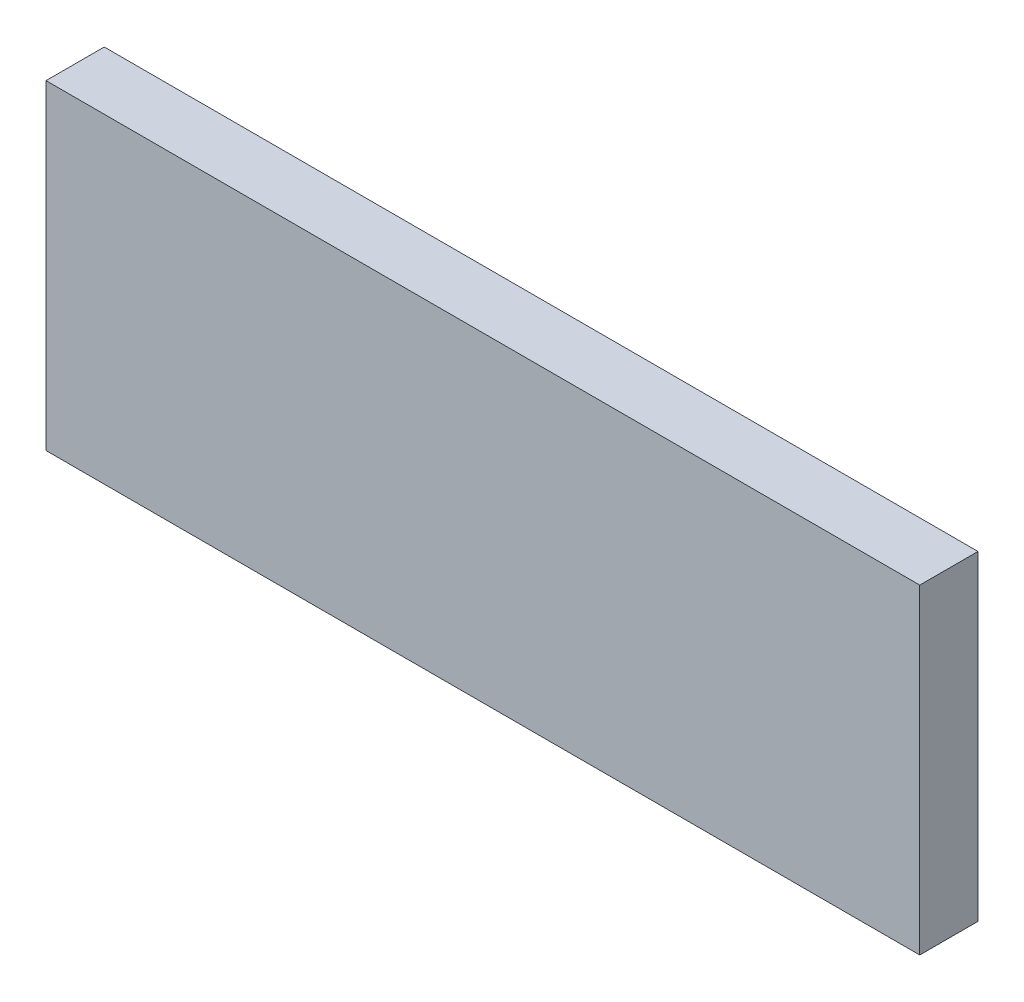
SolidWorks part; units mm, degrees
ref_plane "Front Plane" through (0, 0, 0) normal (0, 0, 1) x (1, 0, 0)
ref_plane "Top Plane" through (0, 0, 0) normal (0, 1, 0) x (1, 0, 0)
ref_plane "Right Plane" through (0, 0, 0) normal (1, 0, 0) x (0, 0, -1)
sketch "Sketch1" plane through (0, 0, 0) normal (0, 0, 1) x (1, 0, 0)
  line L1 (-51.24, 31.58) -> (-21.24, 31.58)
  line L2 (-51.24, 31.58) -> (-51.24, 20.58)
  line L3 (-51.24, 20.58) -> (-21.24, 20.58)
  line L4 (-21.24, 31.58) -> (-21.24, 20.58)
  dimension "D1" = 30
  dimension "D2" = 11
extrude "Boss-Extrude1" add sketch "Sketch1" along normal blind 2
